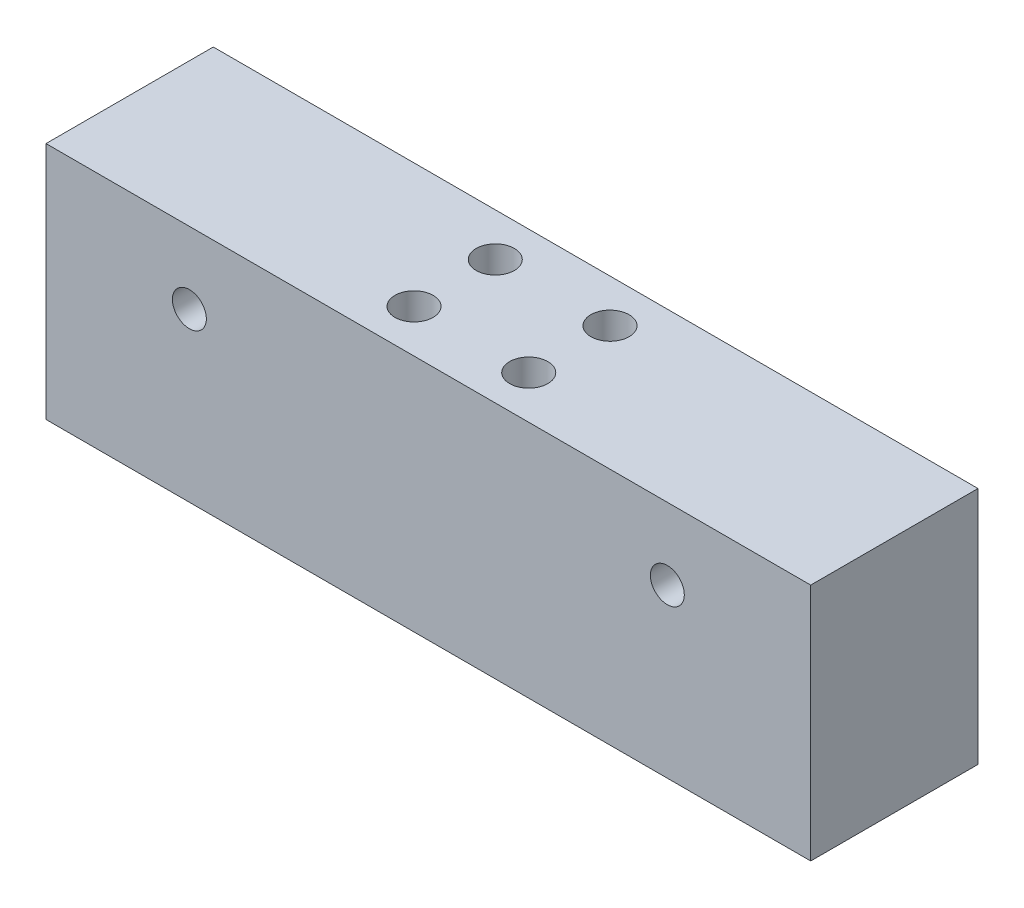
SolidWorks part; units mm, degrees
ref_plane "Front Plane" through (0, 0, 0) normal (0, 0, 1) x (1, 0, 0)
ref_plane "Top Plane" through (0, 0, 0) normal (0, 1, 0) x (1, 0, 0)
ref_plane "Right Plane" through (0, 0, 0) normal (1, 0, 0) x (0, 0, -1)
sketch "Sketch2" plane through (0, 0, 0) normal (0, 0, 1) x (1, 0, 0)
  line L0 (-90.52, 14.235) -> (-90.52, 64.235)
  line L1 (-90.52, 64.235) -> (-25.52, 64.235)
  line L4 (4.48, 64.235) -> (69.48, 64.235)
  line L5 (69.48, 64.235) -> (69.48, 14.235)
  line L7 (-90.52, 14.235) -> (69.48, 14.235)
  line L8 (-10.52, 44.235) -> (-10.52, 14.235) construction
  line L9 (-90.52, 49.235) -> (69.48, 49.235) construction
  line L10 (-25.52, 64.235) -> (4.48, 64.235)
  circle A2 centre (-60.52, 49.235) radius 3.55
  circle A3 centre (39.48, 49.235) radius 3.55
  dimension "D10" = 7.1
  dimension "D11" = 7.1
  dimension "D1" = 160
  dimension "D2" = 50
  dimension "D3" = 20
  dimension "D13" = 50
extrude "Boss-Extrude1" add sketch "Sketch2" along normal blind 35
sketch "Sketch3" plane through (0, 14.235, 0) normal (0, -1, 0) x (1, 0, 0)
  line L8 (-10.52, 31.5) -> (-10.52, 3.5) construction
  line L9 (-28.02, 3.5) -> (6.98, 3.5)
  line L10 (-28.02, 3.5) -> (-28.02, 31.5)
  line L11 (-28.02, 31.5) -> (6.98, 31.5)
  line L12 (6.98, 3.5) -> (6.98, 31.5)
  line L13 (-28.02, 17.5) -> (6.98, 17.5) construction
  line L14 (-22.52, 26) -> (-22.52, 9) construction
  line L15 (1.48, 26) -> (1.48, 9) construction
  line L26 (69.48, 35) -> (69.48, 0) construction
  line L27 (-10.52, 35) -> (-10.52, 0) construction
  line L28 (-90.52, 0) -> (69.48, 0) construction
  line L29 (-90.52, 35) -> (69.48, 35) construction
  line L32 (-90.52, 0) -> (69.48, 0) construction
  circle A4 centre (-22.52, 26) radius 2.25
  circle A5 centre (1.48, 26) radius 2.25
  circle A6 centre (-22.52, 9) radius 2.25
  circle A7 centre (1.48, 9) radius 2.25
  dimension "D15" = 4.5
  dimension "D16" = 4.5
  dimension "D17" = 4.5
  dimension "D25" = 4.5
  dimension "D12" = 28
  dimension "D13" = 35
  dimension "D18" = 24
  dimension "D19" = 24
  dimension "D20" = 17
  dimension "D21" = 8.5
  dimension "D22" = 12
  dimension "D36" = 3.5
  dimension "D40" = 17.5
extrude "Cut-Extrude1" cut sketch "Sketch3" against normal through all
sketch "Sketch5" plane through (0, 64.235, 0) normal (0, 1, 0) x (1, 0, 0)
  circle A0 centre (-22.52, -9) radius 4
  circle A1 centre (-22.52, -26) radius 4
  circle A2 centre (1.48, -26) radius 4
  circle A3 centre (1.48, -9) radius 4
  dimension "D1" = 8
  dimension "D2" = 8
  dimension "D3" = 8
  dimension "D4" = 8
extrude "Cut-Extrude3" cut sketch "Sketch5" against normal blind 10
sketch "Sketch6" plane through (0, 0, 35) normal (0, 0, 1) x (1, 0, 0)
  line L0 (-90.52, 30.8841) -> (69.48, 30.8841) construction
  line L1 (-90.52, 64.235) -> (-90.52, 14.235) construction
  line L2 (69.48, 14.235) -> (69.48, 64.235) construction
equation "\"SyringeDiameter\"= 20"
equation "\"SyringeLength\"= 100"
equation "\"PlungerDiameter\"= 5"
equation "\"PlungerLength\"= 110"
equation "\"VSlotWidth\"= 30"
equation "\"VSlotDepth\"= 20"
equation "\"FingerFlangeDiameter\"= 30"
equation "\"VSlotBackPlateThickness\"= 5"
equation "\"GuideRodDiameter\"= 8.5"
equation "\"LeadScrewDiameter\"= 8.5"
equation "\"GuideRodSpacing\"= 16.25 + 4"
equation "\"LeadScrewSpacing\"= 10.25 + 4"
equation "\"ThreadedInsertDiameter\"= 7.1"
equation "\"ThreadedInsertDepth\"= 10"
equation "\"MountingHoleDiameter\"= 3"
equation "\"MountingHoleSpacing\"= 20"
equation "\"BlockHeight\"= 50"
equation "\"BlockWidth\"= \"RodToScrew\" * 2 + 30"
equation "\"BlockDepth\"= 20"
equation "\"VSlotAngle\"= 90"
equation "\"GuideRodSideWidth\"= 10"
equation "\"ScrewHeight\"= 35"
equation "\"ThreadedInsertSideWidth\"= 50"
equation "\"ScrewMountDistance\"= 25"
equation "\"RodtoRod\"= 115"
equation "\"RodToScrew\"= \"RodtoRod\" / 2"
equation "\"D10@Sketch2\"=\"ThreadedInsertDiameter\""
equation "\"D11@Sketch2\"=\"ThreadedInsertDiameter\""
equation "\"D13@Sketch2\"=\"ThreadedInsertSideWidth\""
equation "\"M4\"= 4.5"
equation "\"D15@Sketch3\"=\"M4\""
equation "\"D16@Sketch3\"=\"M4\""
equation "\"D17@Sketch3\"=\"M4\""
equation "\"D25@Sketch3\"=\"M4\""
